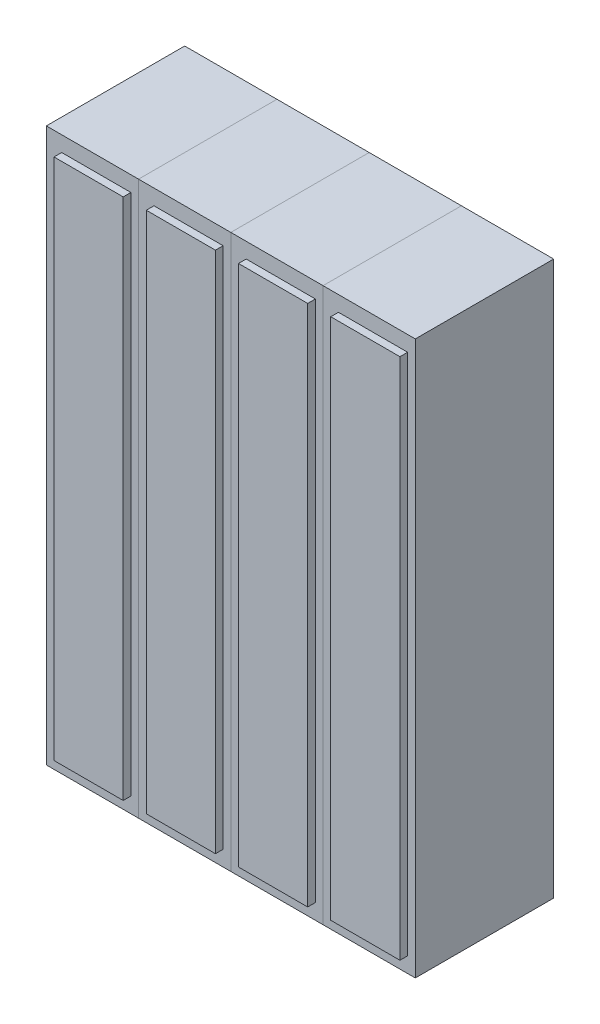
SolidWorks part; units mm, degrees
material "Plain Carbon Steel"
ref_plane "Front Plane" through (0, 0, 0) normal (0, 0, 1) x (1, 0, 0)
ref_plane "Top Plane" through (0, 0, 0) normal (0, 1, 0) x (1, 0, 0)
ref_plane "Right Plane" through (0, 0, 0) normal (1, 0, 0) x (0, 0, -1)
sketch "Sketch1" plane through (0, 0, 0) normal (0, 1, 0) x (1, 0, 0)
  line L1 (0, 0) -> (304.8, 0)
  line L2 (0, 0) -> (0, -457.2)
  line L3 (0, -457.2) -> (304.8, -457.2)
  line L4 (304.8, 0) -> (304.8, -457.2)
  point P6 (0, 0)
  dimension "D1" = 304.8
  dimension "D2" = 457.2
extrude "Boss-Extrude1" add sketch "Sketch1" along normal blind 1828.8
sketch "Sketch2" plane through (0, 0, 457.2) normal (0, 0, 1) x (1, 0, 0)
  line L0 (0, 1828.8) -> (304.8, 1828.8) construction
  line L1 (279.4, 1778) -> (50.8, 1778)
  line L2 (279.4, 1778) -> (279.4, 50.8)
  line L3 (279.4, 50.8) -> (50.8, 50.8)
  line L4 (50.8, 1778) -> (50.8, 50.8)
  line L5 (0, 0) -> (304.8, 0) construction
  line L6 (304.8, 1828.8) -> (304.8, 0) construction
  line L7 (0, 1828.8) -> (0, 0) construction
  dimension "D1" = 50.8
  dimension "D2" = 50.8
  dimension "D3" = 25.4
  dimension "D4" = 50.8
extrude "Boss-Extrude2" add sketch "Sketch2" along normal blind 25.4
pattern_linear "LPattern1" count 4 spacing 304.8 along (1, 0, 0) of bodies 102
